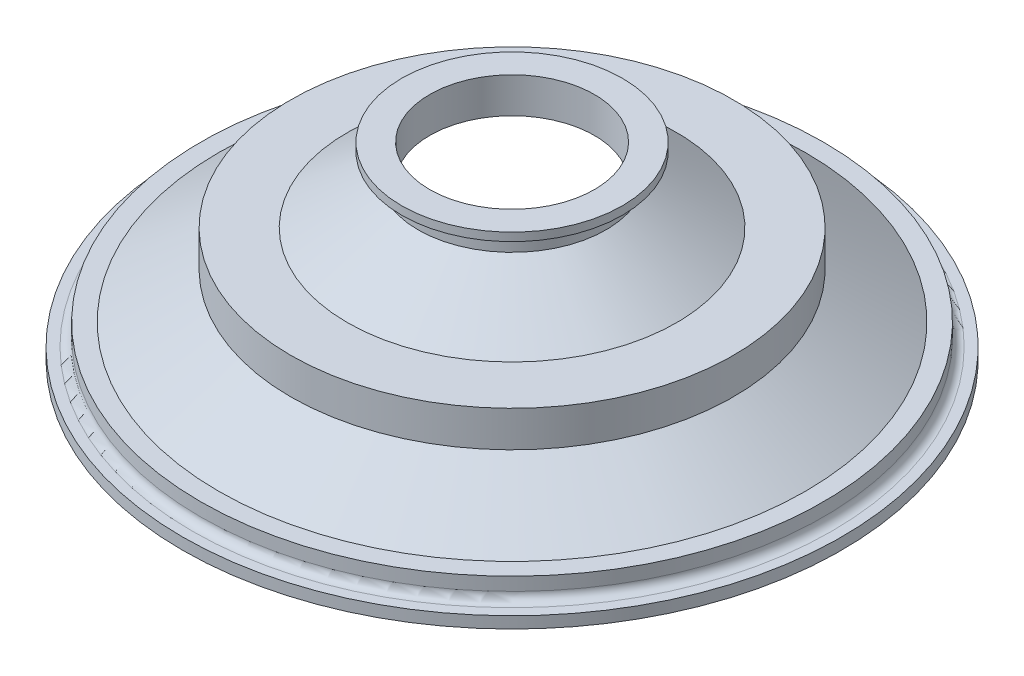
SolidWorks part; units mm, degrees
ref_plane "Front Plane" through (0, 0, 0) normal (0, 0, 1) x (1, 0, 0)
ref_plane "Top Plane" through (0, 0, 0) normal (0, 1, 0) x (1, 0, 0)
ref_plane "Right Plane" through (0, 0, 0) normal (1, 0, 0) x (0, 0, -1)
sketch "Sketch1" plane through (0, 0, 0) normal (0, 0, 1) x (1, 0, 0)
  line L5 (-88, 0) -> (88, 0) construction
  line L6 (88, 6.5) -> (56.8269, 26.2924)
  line L8 (56.8269, 26.2924) -> (63.6633, 26.2924)
  line L9 (63.6633, 26.2924) -> (63.6633, 31.2924)
  line L10 (63.6633, 31.2924) -> (48.9519, 31.2924)
  line L11 (48.9519, 31.2924) -> (25, 46.5)
  line L12 (88, 6.5) -> (91, 6.5)
  line L14 (91, 6.5) -> (91, 6)
  line L15 (97, 0) -> (100, 0)
  line L16 (97, 3.5) -> (100, 3.5)
  line L17 (94.5, 10) -> (94.5, 6)
  line L18 (89.0173, 10) -> (94.5, 10)
  line L19 (89.0173, 10) -> (67.1633, 23.8755)
  line L20 (67.1633, 23.8755) -> (67.1633, 23.8755)
  line L21 (67.1633, 23.8755) -> (67.1633, 34.7924)
  line L22 (67.1633, 34.7924) -> (49.9692, 34.7924)
  line L23 (49.9692, 34.7924) -> (28.5, 48.4237)
  line L24 (100, 3.5) -> (100, 0)
  line L25 (25, 46.5) -> (25, 57.2737)
  line L26 (25, 57.2737) -> (33.5, 57.2737)
  line L27 (33.5, 57.2737) -> (33.5, 54.7737)
  line L28 (33.5, 54.7737) -> (28.5, 54.7737)
  line L29 (28.5, 54.7737) -> (28.5, 48.4237)
  line L30 (49.9692, 34.7924) -> (26.876, 49.4547) construction
  arc A0 (91, 6) -> (97, 0) centre (97, 6) ccw
  arc A1 (94.5, 6) -> (97, 3.5) centre (97, 6) ccw
  point P3 (0, 0)
  dimension "D8" = 6
  dimension "D1" = 176
  dimension "D2" = 12
  dimension "D3" = 25
  dimension "D4" = 40
  dimension "D5" = 6.5
  dimension "D6" = 5
  dimension "D7" = 3
  dimension "D10" = 6.35
  dimension "D11" = 3.5
  dimension "D12" = 2.5
  dimension "D13" = 5
  dimension "D14" = 54.7737
  dimension "D9" = 3.5
ref_axis "Axis1" through (0, 60.1373, 0) along (0, -1, 0)
revolve "Revolve1" add sketch "Sketch1" angle 360 about axis through (0, 60.1373, 0) along (0, -1, 0)
